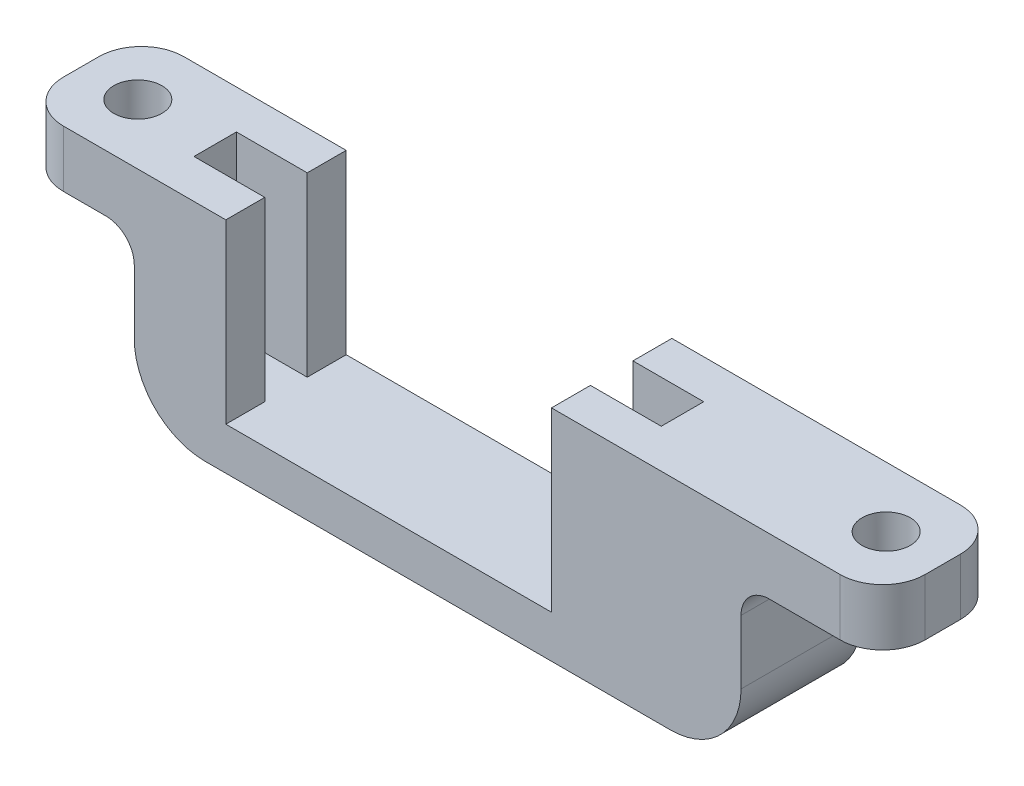
SolidWorks part; units mm, degrees
ref_plane "Front Plane" through (0, 0, 0) normal (0, 0, 1) x (1, 0, 0)
ref_plane "Top Plane" through (0, 0, 0) normal (0, 1, 0) x (1, 0, 0)
ref_plane "Right Plane" through (0, 0, 0) normal (1, 0, 0) x (0, 0, -1)
sketch "Sketch1" plane through (0, 0, 0) normal (0, 1, 0) x (1, 0, 0)
  line L1 (-30.425, 4.25) -> (30.425, 4.25)
  line L2 (-30.425, 4.25) -> (-30.425, -4.25)
  line L3 (-30.425, -4.25) -> (30.425, -4.25)
  line L4 (30.425, 4.25) -> (30.425, -4.25)
  line L5 (-30.425, 4.25) -> (30.425, -4.25) construction
  line L6 (-30.425, -4.25) -> (30.425, 4.25) construction
  point P0 (0, 0)
  dimension "D1" = 8.5
  dimension "D2" = 60.85
extrude "Boss-Extrude1" add sketch "Sketch1" along normal blind 15.5
sketch "Sketch4" plane through (0, 15.5, 0) normal (0, 1, 0) x (1, 0, 0)
  line L0 (-30.425, 0) -> (30.425, 0) construction
  line L1 (30.425, -4.25) -> (30.425, 4.25) construction
  line L2 (-30.425, 4.25) -> (-30.425, -4.25) construction
  line L3 (0, 4.25) -> (0, -4.25) construction
  line L4 (30.425, 4.25) -> (-30.425, 4.25) construction
  line L5 (-30.425, -4.25) -> (30.425, -4.25) construction
  circle A0 centre (-26.425, 0) radius 1.7
  circle A2 centre (26.425, 0) radius 1.7
  point P13 (-30.425, 0)
  dimension "D1" = 3.4
  dimension "D3" = 4
extrude "Cut-Extrude3" cut sketch "Sketch4" against normal through all
sketch "Sketch2" plane through (0, 15.5, 0) normal (0, 1, 0) x (1, 0, 0)
  line L0 (-30.425, 0) -> (30.425, 0) construction
  line L1 (-30.425, 4.25) -> (-30.425, -4.25) construction
  line L2 (30.425, -4.25) -> (30.425, 4.25) construction
  line L3 (-15.96, -4.25) -> (7.04, -4.25)
  line L8 (-15.96, -4.25) -> (-15.96, 4.25)
  line L9 (-15.96, 4.25) -> (7.04, 4.25)
  line L10 (7.04, -4.25) -> (7.04, 4.25)
  line L11 (-15.96, -4.25) -> (7.04, 4.25) construction
  line L12 (-15.96, 4.25) -> (7.04, -4.25) construction
  line L13 (-20.96, -1.5) -> (-15.96, -1.5)
  line L14 (-20.96, -1.5) -> (-20.96, 1.5)
  line L15 (-20.96, 1.5) -> (-15.96, 1.5)
  line L16 (-15.96, -1.5) -> (-15.96, 1.5)
  line L17 (-20.96, -1.5) -> (-15.96, 1.5) construction
  line L18 (-20.96, 1.5) -> (-15.96, -1.5) construction
  line L23 (-4.46, 4.25) -> (-4.46, -4.25) construction
  line L24 (12.04, 1.5) -> (7.04, -1.5) construction
  line L25 (30.425, 4.25) -> (-30.425, 4.25) construction
  line L26 (12.04, -1.5) -> (7.04, 1.5) construction
  line L27 (7.04, -1.5) -> (7.04, 1.5)
  line L28 (12.04, 1.5) -> (7.04, 1.5)
  line L29 (12.04, -1.5) -> (12.04, 1.5)
  line L30 (12.04, -1.5) -> (7.04, -1.5)
  point P2 (-4.46, 0)
  point P10 (-18.46, 0)
  point P23 (9.54, 0)
  dimension "D1" = 4.46
  dimension "D2" = 3
  dimension "D3" = 23
  dimension "D4" = 5
extrude "Cut-Extrude1" cut sketch "Sketch2" against normal blind 12.5
sketch "Sketch3" plane through (0, 0, 0) normal (0, -1, 0) x (1, 0, 0)
  line L0 (30.425, -4.25) -> (-30.425, -4.25) construction
  line L1 (-30.425, 4.25) -> (-22.425, 4.25)
  line L2 (-30.425, 4.25) -> (-30.425, -4.25)
  line L3 (-30.425, -4.25) -> (-22.425, -4.25)
  line L4 (-22.425, 4.25) -> (-22.425, -4.25)
  line L6 (30.425, 4.25) -> (20.425, 4.25)
  line L7 (30.425, 4.25) -> (30.425, -4.25)
  line L8 (30.425, -4.25) -> (20.425, -4.25)
  line L9 (20.425, 4.25) -> (20.425, -4.25)
  dimension "D1" = 10
  dimension "D2" = 8
extrude "Cut-Extrude2" cut sketch "Sketch3" against normal blind 11.5
fillet "Fillet1" radius 2 2 edges at (-22.425, 11.5, 0) (20.425, 11.5, 0)
fillet "Fillet2" radius 3 4 edges at (30.425, 13.5, -4.25) (30.425, 13.5, 4.25) (-30.425, 13.5, -4.25) (-30.425, 13.5, 4.25)
fillet "Fillet3" radius 5 2 edges at (-22.425, 0, 0) (20.425, 0, 0)
